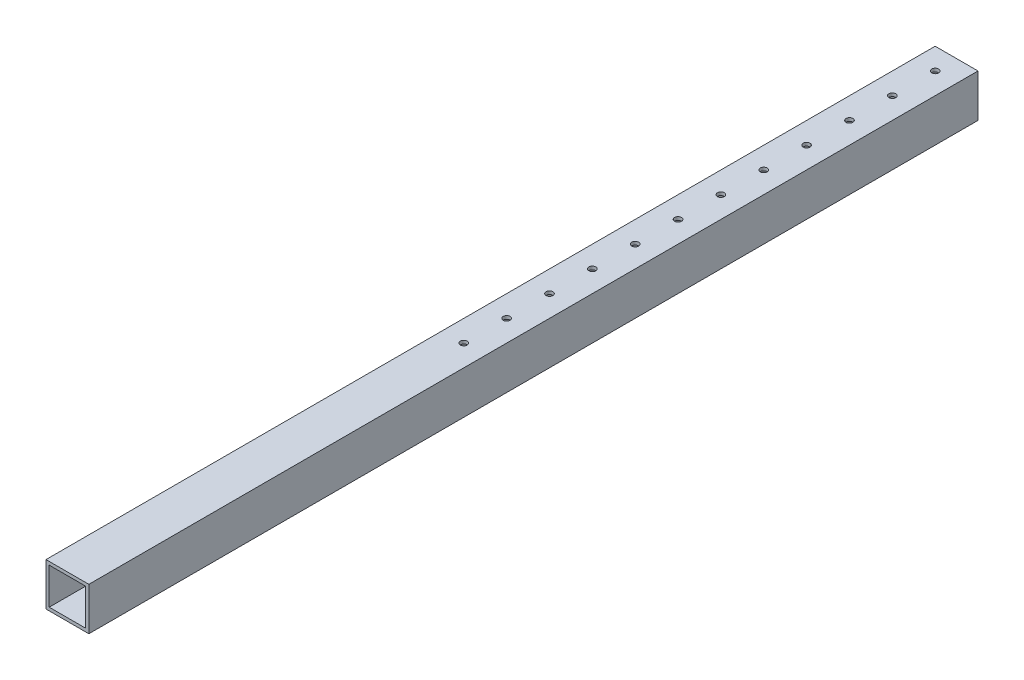
SolidWorks part; units mm, degrees
material "6061 合金"
ref_plane "前视基准面" through (0, 0, 0) normal (0, 0, 1) x (1, 0, 0)
ref_plane "上视基准面" through (0, 0, 0) normal (0, 1, 0) x (1, 0, 0)
ref_plane "右视基准面" through (0, 0, 0) normal (1, 0, 0) x (0, 0, -1)
other "Configuration Table"
sketch "草图1" plane through (0, 0, 0) normal (0, 0, 1) x (1, 0, 0)
  line L1 (-8.5, 8.5) -> (8.5, 8.5)
  line L2 (-8.5, 8.5) -> (-8.5, -8.5)
  line L3 (-8.5, -8.5) -> (8.5, -8.5)
  line L4 (8.5, 8.5) -> (8.5, -8.5)
  line L5 (-8.5, 8.5) -> (8.5, -8.5) construction
  line L6 (-8.5, -8.5) -> (8.5, 8.5) construction
  line L7 (-10, 10) -> (10, 10)
  line L8 (-10, 10) -> (-10, -10)
  line L9 (-10, -10) -> (10, -10)
  line L10 (10, 10) -> (10, -10)
  line L11 (-10, 10) -> (10, -10) construction
  line L12 (-10, -10) -> (10, 10) construction
  point P0 (0, 0)
  point P6 (0, 0)
  dimension "D1" = 20
  dimension "D2" = 20
  dimension "D3" = 1.5
  dimension "D4" = 1.5
extrude "凸台-拉伸1" add sketch "草图1" along normal blind 415
sketch "草图2" [suppressed] plane through (0, 10, 0) normal (0, 1, 0) x (1, 0, 0)
  line L0 (0, 0) -> (0, -50000) construction
  line L1 (10, 0) -> (-10, 0) construction
  line L2 (10, -342.12) -> (-10, -342.12) construction
  circle A0 centre (0, -5) radius 1.5
  circle A1 centre (0, -20) radius 1.5
  circle A2 centre (0, -337.12) radius 1.5
  circle A3 centre (0, -322.12) radius 1.5
  dimension "D1" = 5
  dimension "D2" = 15
  dimension "D3" = 3
  dimension "D4" = 5
  dimension "D5" = 15
extrude "切除-拉伸1" [suppressed] cut sketch "草图2" against normal through all
sketch "草图3" [suppressed] plane through (0, 10, 0) normal (0, 1, 0) x (1, 0, 0)
  line L0 (0, 0) -> (0, -50000) construction
  line L1 (0, -35) -> (0, -50) construction
  circle A0 centre (0, -35) radius 1.5
  circle A1 centre (0, -50) radius 1.5
  circle A2 centre (0, -65) radius 1.5
  circle A3 centre (0, -80) radius 1.5
  circle A4 centre (0, -95) radius 1.5
  circle A5 centre (0, -110) radius 1.5
  circle A6 centre (0, -125) radius 1.5
  circle A7 centre (0, -140) radius 1.5
  circle A8 centre (0, -155) radius 1.5
  circle A9 centre (0, -170) radius 1.5
  circle A10 centre (0, -185) radius 1.5
  circle A11 centre (0, -200) radius 1.5
  circle A12 centre (0, -215) radius 1.5
  circle A13 centre (0, -230) radius 1.5
  circle A14 centre (0, -245) radius 1.5
  circle A15 centre (0, -260) radius 1.5
  circle A16 centre (0, -275) radius 1.5
  circle A17 centre (0, -290) radius 1.5
  circle A18 centre (0, -305) radius 1.5
  circle A19 centre (0, -20) radius 1.5 construction
  dimension "D3" = 3
  dimension "D4" = 15
  dimension "D2" = 15
  dimension "D1" = 19
extrude "切除-拉伸2" [suppressed] cut sketch "草图3" against normal through all
sketch "草图4" [suppressed] plane through (-10, 0, 0) normal (-1, 0, 0) x (0, 0, 1)
  line L0 (235.04, 0) -> (-49764.96, 0) construction
  line L1 (325.04, 10) -> (325.04, -10) construction
  circle A0 centre (282.54, 0) radius 1.6
  circle A1 centre (302.54, 0) radius 1.6
  point P11 (325.04, 0)
  dimension "D1" = 3.2
  dimension "D2" = 20
  dimension "D3" = 22.5
extrude "切除-拉伸3" [suppressed] cut sketch "草图4" against normal through all
sketch "草图5" plane through (0, -10, 0) normal (0, -1, 0) x (1, 0, 0)
  line L0 (0, 0) -> (0, -50000) construction
  line L1 (-10, 0) -> (10, 0) construction
  line L2 (0, 10) -> (0, 30) construction
  circle A0 centre (0, 10) radius 1.6
  circle A1 centre (0, 30) radius 1.6
  circle A2 centre (0, 50) radius 1.6
  circle A3 centre (0, 70) radius 1.6
  circle A4 centre (0, 90) radius 1.6
  circle A5 centre (0, 110) radius 1.6
  circle A6 centre (0, 130) radius 1.6
  circle A7 centre (0, 150) radius 1.6
  circle A8 centre (0, 170) radius 1.6
  circle A9 centre (0, 190) radius 1.6
  circle A10 centre (0, 210) radius 1.6
  circle A11 centre (0, 230) radius 1.6
  dimension "D1" = 10
  dimension "D2" = 3.2
  dimension "D4" = 20
  dimension "D3" = 12
extrude "切除-拉伸4" cut sketch "草图5" against normal through all
sketch "草图6" [suppressed] plane through (0, 10, 0) normal (0, 1, 0) x (1, 0, 0)
  line L0 (0, 0) -> (0, -50000) construction
  line L1 (10, 0) -> (-10, 0) construction
  line L2 (0, -10) -> (0, -30) construction
  circle A0 centre (0, -10) radius 1.5
  circle A1 centre (0, -30) radius 1.5
  circle A2 centre (0, -50) radius 1.5
  circle A3 centre (0, -70) radius 1.5
  circle A4 centre (0, -90) radius 1.5
  circle A5 centre (0, -110) radius 1.5
  circle A6 centre (0, -130) radius 1.5
  circle A7 centre (0, -150) radius 1.5
  dimension "D1" = 3
  dimension "D2" = 10
  dimension "D4" = 20
  dimension "D3" = 8
extrude "切除-拉伸5" [suppressed] cut sketch "草图6" against normal through all
